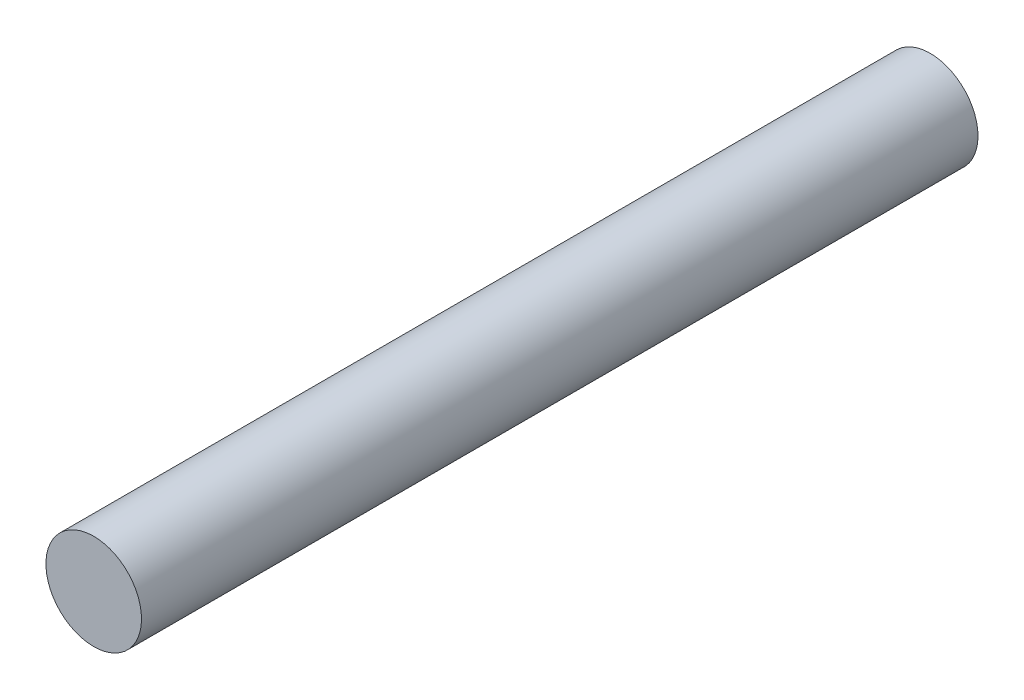
SolidWorks part; units mm, degrees
material "1023 Tôle d'acier au carbone (SS)"
ref_plane "Plan de face" through (0, 0, 0) normal (0, 0, 1) x (1, 0, 0)
ref_plane "Plan de dessus" through (0, 0, 0) normal (0, 1, 0) x (1, 0, 0)
ref_plane "Plan de droite" through (0, 0, 0) normal (1, 0, 0) x (0, 0, -1)
sketch "Esquisse1" plane through (0, 0, 0) normal (0, 0, 1) x (1, 0, 0)
  circle A0 centre (0, 0) radius 4
  dimension "D1" = 8
extrude "Boss.-Extru.1" add sketch "Esquisse1" along normal blind 70
